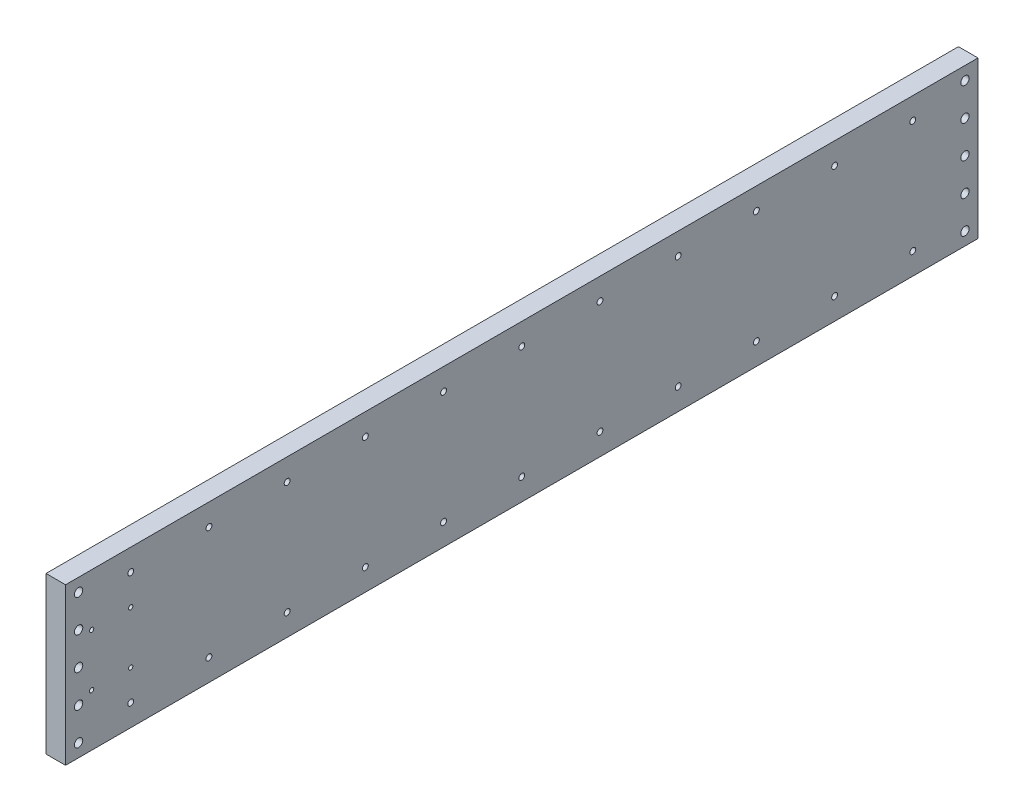
SolidWorks part; units mm, degrees
ref_plane "Front Plane" through (0, 0, 0) normal (0, 0, 1) x (1, 0, 0)
ref_plane "Top Plane" through (0, 0, 0) normal (0, 1, 0) x (1, 0, 0)
ref_plane "Right Plane" through (0, 0, 0) normal (1, 0, 0) x (0, 0, -1)
sketch "Sketch2" plane through (0, 0, 0) normal (0, 0, 1) x (1, 0, 0)
  line L0 (-15, 0) -> (0, 0)
  line L3 (0, 0) -> (0, -120)
  line L4 (0, -120) -> (-15, -120)
  line L5 (-15, -120) -> (-15, 0)
  dimension "D1" = 120
  dimension "D2" = 15
extrude "Boss-Extrude1" add sketch "Sketch2" along normal blind 700
sketch "Sketch7" plane through (0, 0, 0) normal (1, 0, 0) x (0, 0, -1)
  line L0 (-700, -60) -> (0, -60) construction
  line L2 (-700, -16.7) -> (0, -16.7) construction
  line L4 (-700, 0) -> (0, 0) construction
  line L5 (-700, -120) -> (-700, 0) construction
  point P4 (-50, -103.3)
  point P7 (-110, -103.3)
  point P8 (-170, -103.3)
  point P11 (-650, -16.7)
  point P13 (-590, -16.7)
  point P14 (-530, -16.7)
  point P15 (-470, -16.7)
  point P16 (-410, -16.7)
  point P17 (-350, -16.7)
  point P18 (-290, -16.7)
  point P19 (-230, -16.7)
  point P20 (-170, -16.7)
  point P29 (-110, -16.7)
  point P30 (-50, -16.7)
  point P32 (-230, -103.3)
  point P35 (-290, -103.3)
  point P36 (-350, -103.3)
  point P37 (-410, -103.3)
  point P38 (-470, -103.3)
  point P39 (-530, -103.3)
  point P40 (-590, -103.3)
  point P41 (-650, -103.3)
  dimension "D1" = 16.7
  dimension "D2" = 50
  dimension "D3" = 11
hole_wizard "Ø4.5 (4.5) Diameter Hole1" positions "3DSketch3" profile "Sketch8" hole size "Ø4.5" standard "ISO" end condition through all
sketch3d "3DSketch3"
  point P0 (0, -16.7, 650)
  point P3 (0, -16.7, 590)
  point P6 (0, -16.7, 530)
  point P9 (0, -16.7, 470)
  point P12 (0, -16.7, 410)
  point P15 (0, -16.7, 350)
  point P18 (0, -16.7, 290)
  point P21 (0, -16.7, 230)
  point P24 (0, -16.7, 170)
  point P54 (0, -16.7, 110)
  point P57 (0, -16.7, 50)
  point P64 (0, -103.3, 650)
  point P67 (0, -103.3, 590)
  point P70 (0, -103.3, 530)
  point P73 (0, -103.3, 470)
  point P76 (0, -103.3, 410)
  point P79 (0, -103.3, 350)
  point P82 (0, -103.3, 290)
  point P85 (0, -103.3, 230)
  point P88 (0, -103.3, 170)
  point P91 (0, -103.3, 110)
  point P94 (0, -103.3, 50)
sketch "Sketch8" plane through (0, -16.7, 650) normal (0, 1, 0) x (0, 0, -1)
  line L0 (0, 0) -> (0, 15)
  line L1 (0, 15) -> (2.25, 15)
  line L2 (2.25, 15) -> (2.25, 0)
  line L5 (2.25, 0) -> (0, 0)
  line L11 (0, -6.35) -> (0, 107.95) construction
  dimension "Thru Hole Dia." = 4.5
  dimension "Thru Hole Depth" = 15
sketch "Sketch9" plane through (0, 0, 0) normal (1, 0, 0) x (0, 0, -1)
  line L0 (-700, -40) -> (-650, -40) construction
  line L1 (-504.5233, -37.9) -> (-462.0233, -37.9) construction
  line L2 (-504.5233, -42.1) -> (-462.0233, -42.1) construction
  line L3 (-700, -120) -> (-700, 0) construction
  point P12 (-650, -40)
  point P13 (-680, -40)
  point P18 (-680, -80)
  point P19 (-650, -80)
  dimension "D1" = 20
  dimension "D2" = 30
  dimension "D3" = 40
hole_wizard "M4 Tapped Hole3" positions "3DSketch5" profile "Sketch11" tap size "M4" standard "ISO" end condition through all
sketch3d "3DSketch5"
  point P0 (0, -40, 680)
  point P3 (0, -40, 650)
  point P6 (0, -80, 680)
  point P9 (0, -80, 650)
sketch "Sketch11" plane through (0, -40, 680) normal (0, 1, 0) x (0, 0, -1)
  line L0 (0, 0) -> (0, 15)
  line L1 (0, 15) -> (1.65, 15)
  line L2 (1.65, 15) -> (1.65, 0)
  line L5 (1.65, 0) -> (0, 0)
  line L11 (0, -6.35) -> (0, 107.95) construction
  dimension "Thread Major Dia." = 3.3
  dimension "Thru Tap Drill Depth" = 15
sketch "Sketch12" plane through (-15, 0, 0) normal (1, 0, 0) x (0, 0, -1)
  line L0 (-690, 0) -> (-690, -120) construction
  line L1 (-700, 0) -> (0, 0) construction
  line L2 (-700, -120) -> (0, -120) construction
  line L3 (-700, -120) -> (-700, 0) construction
  line L4 (-700, -60) -> (-669.8028, -60) construction
  line L5 (-700, -60) -> (0, -60) construction
  line L6 (-350, 0) -> (-350, -120) construction
  point P13 (-690, -60)
  point P15 (-690, -85)
  point P16 (-690, -35)
  point P17 (-690, -10)
  point P18 (-690, -110)
  point P19 (-10, -110)
  point P20 (-10, -10)
  point P22 (-10, -35)
  point P23 (-10, -85)
  point P24 (-10, -60)
  dimension "D1" = 10
  dimension "D2" = 3
hole_wizard "CBORE for M6 SHCS1" positions "3DSketch7" profile "Sketch14" counterbore size "M6" standard "ANSI Metric" end condition through all
sketch3d "3DSketch7"
  line L0 (-15, 0, 690) -> (-15, -120, 690) construction
  point P0 (-15, -10, 690)
  point P3 (-15, -60, 690)
  point P7 (-15, -35, 690)
  point P10 (-15, -85, 690)
  point P13 (-15, -110, 690)
  point P16 (-15, -60, 690)
  point P18 (-15, -60, 690)
  point P20 (-15, -60, 690)
  point P22 (-15, -60, 690)
  point P25 (-15, -10, 10)
  point P28 (-15, -35, 10)
  point P31 (-15, -60, 10)
  point P34 (-15, -85, 10)
  point P37 (-15, -110, 10)
sketch "Sketch14" plane through (-15, -10, 690) normal (0, 1, 0) x (0, 0, 1)
  line L0 (0, 0) -> (0, 15)
  line L1 (0, 15) -> (3.2, 15)
  line L3 (3.2, 15) -> (3.2, 6)
  line L4 (3.2, 6) -> (5.5, 6)
  line L5 (5.5, 6) -> (5.5, 0)
  line L7 (5.5, 0) -> (0, 0)
  line L11 (0, -6.35) -> (0, 107.95) construction
  dimension "Thru Hole Dia." = 6.4
  dimension "Thru Hole Depth" = 15
  dimension "C'Bore Dia." = 11
  dimension "C'Bore Depth" = 6
